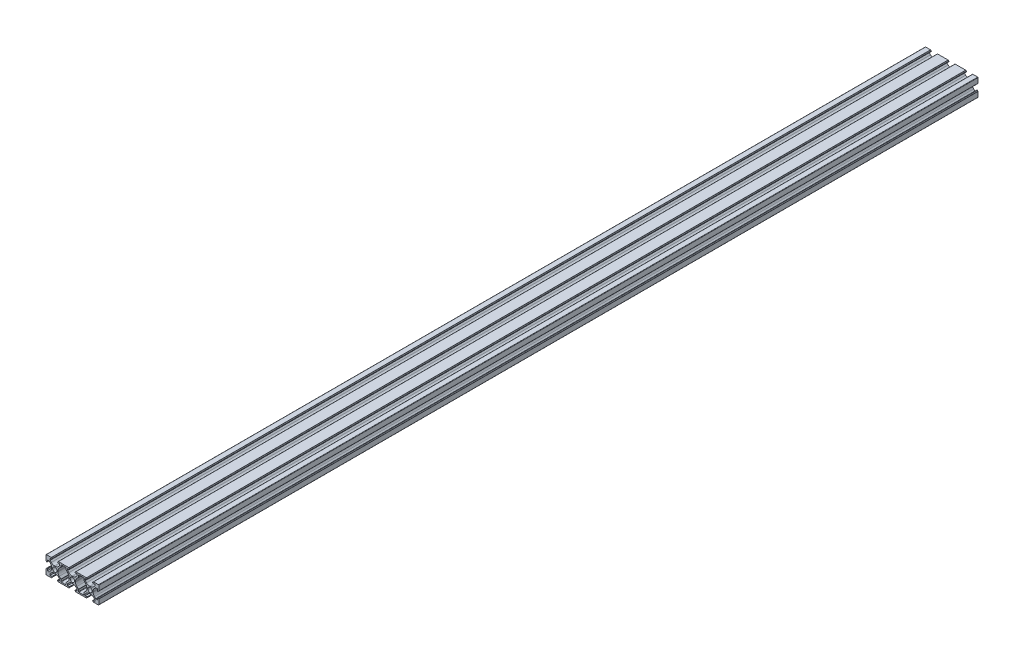
SolidWorks part; units mm, degrees
ref_plane "Plano frontal" through (0, 0, 0) normal (0, 0, 1) x (1, 0, 0)
ref_plane "Plano superior" through (0, 0, 0) normal (0, 1, 0) x (1, 0, 0)
ref_plane "Plano direito" through (0, 0, 0) normal (1, 0, 0) x (0, 0, -1)
sketch "Esboço1" plane through (0, 0, 0) normal (0, 0, 1) x (1, 0, 0)
  line L0 (-9.0343, 3.1) -> (-8.9, 3.1)
  line L3 (-10, 10) -> (-4.0657, 10)
  line L5 (-10, -10) -> (10, 10) construction
  line L6 (-10, 10) -> (10, -10) construction
  line L7 (-8.5, 3.5) -> (-8.5, 5.5)
  line L8 (-10, 0) -> (10, 0) construction
  line L9 (0, 10) -> (0, -10) construction
  line L12 (-8.5, 5.5) -> (-6.5607, 5.5)
  line L15 (-6.5607, 5.5) -> (-5.0645, 4.0038)
  line L16 (-3.6, 0.4683) -> (-3.6, 0)
  line L17 (-0.4683, 3.6) -> (0, 3.6)
  line L18 (-5.5, 6.5607) -> (-4.0038, 5.0645)
  line L21 (-5.5, 8.5) -> (-5.5, 6.5607)
  line L24 (-3.5, 8.5) -> (-5.5, 8.5)
  line L25 (-3.1, 9.0343) -> (-3.1, 8.9)
  line L44 (-10, 4.0657) -> (-10, 10)
  line L45 (-9.8828, 3.7828) -> (-9.3172, 3.2172)
  line L46 (-3.7828, 9.8828) -> (-3.2172, 9.3172)
  line L47 (-3.6, 0) -> (-2.5, 0)
  line L48 (0, 3.6) -> (0, 2.5)
  arc A0 (-3.5, 8.5) -> (-3.1, 8.9) centre (-3.5, 8.9) ccw
  arc A1 (-3.7828, 9.8828) -> (-4.0657, 10) centre (-4.0657, 9.6) ccw
  arc A2 (-10, 4.0657) -> (-9.8828, 3.7828) centre (-9.6, 4.0657) ccw
  arc A3 (-8.5, 3.5) -> (-8.9, 3.1) centre (-8.9, 3.5) cw
  arc A4 (-3.2172, 9.3172) -> (-3.1, 9.0343) centre (-3.5, 9.0343) cw
  arc A5 (-9.3172, 3.2172) -> (-9.0343, 3.1) centre (-9.0343, 3.5) ccw
  arc A6 (-3.6, 0.4683) -> (-5.0645, 4.0038) centre (-8.6, 0.4683) ccw
  arc A7 (-4.0038, 5.0645) -> (-0.4683, 3.6) centre (-0.4683, 8.6) ccw
  circle A8 centre (0, 0) radius 2.5
  point P6 (-10, 3.1)
  point P28 (-3.1, 8.5)
  point P31 (-3.1, 10)
  point P33 (-3.9, 10)
  point P36 (-10, 3.9)
  point P39 (-8.5, 3.1)
  point P42 (-3.1, 9.2)
  point P45 (-9.2, 3.1)
  point P48 (-3.6, 2.5393)
  point P51 (-2.5393, 3.6)
  dimension "D5" = 10
  dimension "D9" = 0.4
  dimension "D10" = 0.4
  dimension "D11" = 5
  dimension "D12" = 5
  dimension "D13" = 5
  dimension "D1" = 6.9
  dimension "D2" = 1.5
  dimension "D3" = 3.6
  dimension "D4" = 1.5
  dimension "D6" = 2.4
  dimension "D7" = 3.6
  dimension "D8" = 45
extrude "Ressalto-extrusão1" add sketch "Esboço1" along normal blind 1000
sketch "Esboço3" plane through (0, 0, 0) normal (1, 0, 0) x (0, 0, -1)
  line L0 (0, 0) -> (-1000, 0) construction
  dimension "D1" = 1000
pattern_circular "PadrãoCircular1" count 4 over 360 about axis through (0, 0, 0) along (0, 0, 1) of "Ressalto-extrusão1"
pattern_linear "Padrão linear1" count 3 spacing 20 along (1, 0, 0) of "Ressalto-extrusão1", "PadrãoCircular1"
sketch "Esboço4" plane through (0, 0, 0) normal (0, 0, -1) x (-1, 0, 0)
  line L0 (-13.4393, 5.5) -> (-13, 5.9393)
  line L1 (-13, 8.5) -> (-13, 5.9393)
  line L2 (-10, 10) -> (-10, -10) construction
  line L3 (-4.0657, 10) -> (-15.9343, 10) construction
  line L4 (-15.9343, -10) -> (-4.0657, -10) construction
  line L5 (-11.5, 5.5) -> (-13.4393, 5.5) construction
  line L6 (-14.5, 8.5) -> (-14.5, 6.5607) construction
  line L7 (-7, 8.5) -> (-7, 5.9393)
  line L8 (-6.5607, 5.5) -> (-7, 5.9393)
  line L9 (-13, 8.5) -> (-7, 8.5)
  line L10 (-20, 0) -> (0, 0) construction
  line L11 (-13, -8.5) -> (-7, -8.5)
  line L12 (-6.5607, -5.5) -> (-7, -5.9393)
  line L13 (-7, -8.5) -> (-7, -5.9393)
  line L14 (-13, -8.5) -> (-13, -5.9393)
  line L15 (-13.4393, -5.5) -> (-13, -5.9393)
  line L16 (-13.4393, 5.5) -> (-13.4393, -5.5)
  line L17 (-6.5607, -5.5) -> (-6.5607, 5.5)
  line L31 (-40, 0) -> (-20, 0) construction
  line L32 (-33.4393, 5.5) -> (-33, 5.9393) [skipped]
  line L33 (-33, 8.5) -> (-33, 5.9393) [skipped]
  line L34 (-27, 8.5) -> (-27, 5.9393) [skipped]
  line L35 (-26.5607, 5.5) -> (-27, 5.9393) [skipped]
  line L36 (-33, 8.5) -> (-27, 8.5) [skipped]
  line L37 (-33, -8.5) -> (-27, -8.5) [skipped]
  line L38 (-26.5607, -5.5) -> (-27, -5.9393) [skipped]
  line L39 (-27, -8.5) -> (-27, -5.9393) [skipped]
  line L40 (-33, -8.5) -> (-33, -5.9393) [skipped]
  line L41 (-33.4393, -5.5) -> (-33, -5.9393) [skipped]
  line L42 (-33.4393, 5.5) -> (-33.4393, -5.5) [skipped]
  line L43 (-26.5607, -5.5) -> (-26.5607, 5.5) [skipped]
  line L44 (-30, 10) -> (-30, -10) construction
  dimension "D1" = 45
  dimension "D2" = 1.5
  dimension "D3" = 1.5
  dimension "D4" = 2
extrude "Corte-extrusão1" cut sketch "Esboço4" against normal through all
pattern_linear "Padrão linear2" count 2 spacing 20 along (1, 0, 0) of "Corte-extrusão1"
fillet "Filete1" radius 0.4 16 edges at (13, -5.9393, 500) (13, -8.5, 500) (7, -8.5, 500) (7, -5.9393, 500) (7, 8.5, 500) (7, 5.9393, 500) (13, 8.5, 500) (13, 5.9393, 500) (27, -8.5, 500) (27, -5.9393, 500) (27, 8.5, 500) (27, 5.9393, 500) (33, 8.5, 500) (33, -8.5, 500) (33, -5.9393, 500) (33, 5.9393, 500)
fillet "Filete2" radius 0.4 4 edges at (-10, 10, 500) (50, -10, 500) (50, 10, 500) (-10, -10, 500)
